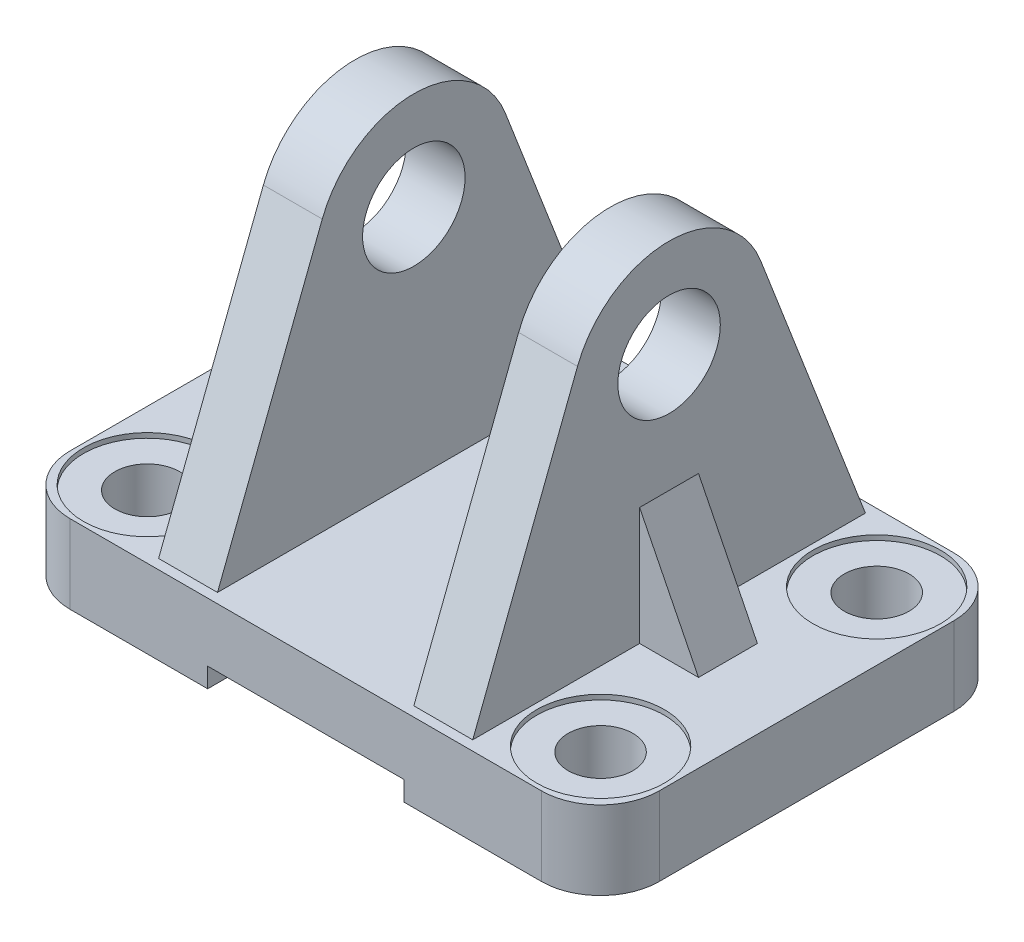
SolidWorks part; units mm, degrees
ref_plane "前视基准面" through (0, 0, 0) normal (0, 0, 1) x (1, 0, 0)
ref_plane "上视基准面" through (0, 0, 0) normal (0, 1, 0) x (1, 0, 0)
ref_plane "右视基准面" through (0, 0, 0) normal (1, 0, 0) x (0, 0, -1)
sketch "草图1" plane through (0, 0, 0) normal (0, 0, 1) x (1, 0, 0)
  line L0 (0, 0) -> (0, 67.8358) construction
  line L1 (-10, 2) -> (10, 2)
  line L2 (10, 2) -> (10, 0)
  line L3 (10, 0) -> (30, 0)
  line L4 (30, 0) -> (30, 8)
  line L5 (30, 8) -> (-30, 8)
  line L6 (-30, 0) -> (-30, 8)
  line L7 (-10, 0) -> (-30, 0)
  line L8 (-10, 2) -> (-10, 0)
  point P10 (0, 8)
  point P13 (0, 2)
  dimension "D1" = 10
  dimension "D2" = 8
  dimension "D3" = 6
  dimension "D4" = 30
extrude "凸台-拉伸1" add sketch "草图1" along normal mid plane 42
ref_plane "基准面1" through (6, 0, 0) normal (1, 0, 0) x (0, 0, -1)
sketch "草图2" plane through (6, 0, 0) normal (1, 0, 0) x (0, 0, -1)
  line L0 (0, 0) -> (0, 30.8476) construction
  line L1 (-20, 8) -> (20, 8)
  line L3 (-21, 8) -> (21, 8) construction
  line L4 (9.3272, 35.606) -> (20, 8)
  line L5 (-9.3272, 35.606) -> (-20, 8)
  arc A0 (9.3272, 35.606) -> (-9.3272, 35.606) centre (0, 32) ccw
  circle A1 centre (0, 32) radius 5.2205
  point P8 (-0.8673, 8.172)
  point P12 (0, 8)
  dimension "D1" = 20
  dimension "D2" = 10
  dimension "D3" = 24
extrude "凸台-拉伸3" add sketch "草图2" along normal blind 6 from offset 4
sketch "草图6" plane through (0, 0, 0) normal (0, 0, 1) x (1, 0, 0)
  line L0 (16, 20) -> (22, 8)
  line L2 (30, 8) -> (-30, 8) construction
  dimension "D1" = 6
  dimension "D2" = 12
rib "筋1" sketch "草图6" sketch "草图6" thickness 6 extrusion direction parallel to sketch draft on no parameters "D1"=6
fillet "圆角1" radius 6 1 edges at (30, 4, 21)
fillet "圆角2" radius 6 1 edges at (30, 4, -21)
hole_wizard "打孔尺寸(%根据六角头螺)栓 C 级的类型3" positions "草图12" profile "草图11" counterbore size "M6" standard "GB" end condition up to next
sketch "草图12" plane through (0, 8, 0) normal (0, 1, 0) x (1, 0, 0)
  point P0 (23.0864, -14.0652)
sketch "草图11" plane through (23.0864, 8, 14.0652) normal (1, 0, 0) x (0, 0, 1)
  line L0 (0, 0) -> (0, 8)
  line L1 (0, 8) -> (3.3, 8)
  line L3 (3.3, 8) -> (3.3, 0.5)
  line L4 (3.3, 0.5) -> (6.5, 0.5)
  line L5 (6.5, 0.5) -> (6.5, 0)
  line L7 (6.5, 0) -> (0, 0)
  line L11 (0, -6.35) -> (0, 107.95) construction
  dimension "通孔孔直径" = 6.6
  dimension "通孔孔深度" = 8
  dimension "柱形沉头孔直径" = 13
  dimension "柱形沉头孔深度" = 0.5
mirror "镜向1" about plane through (0, 0, 0) normal (1, 0, 0) of "打孔尺寸(%根据六角头螺)栓 C 级的类型3", "凸台-拉伸3", "筋1"
fillet "圆角3" radius 6 1 edges at (-30, 4, 21)
fillet "圆角4" radius 6 1 edges at (-30, 4, -21)
mirror "镜向2" about plane through (0, 0, 0) normal (0, 0, 1) of "打孔尺寸(%根据六角头螺)栓 C 级的类型3"
mirror "镜向6" about plane through (0, 0, 0) normal (1, 0, 0) of "镜向2"
